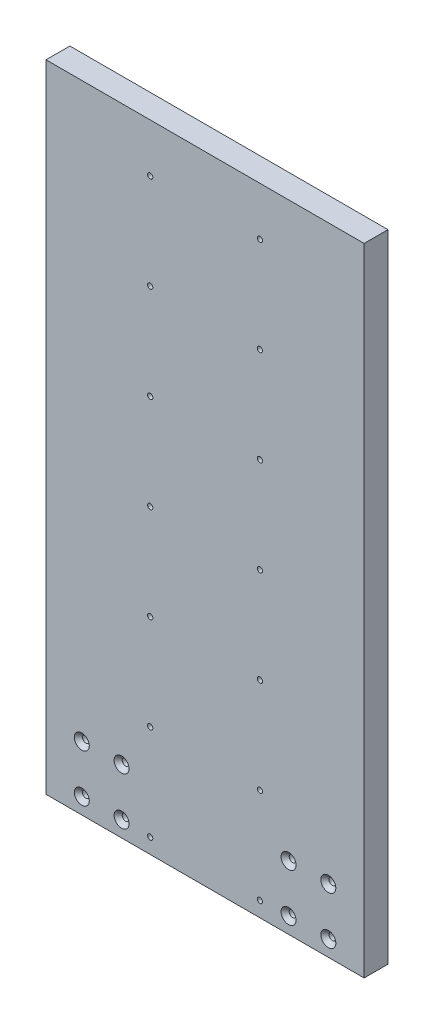
SolidWorks part; units mm, degrees
ref_plane "Front Plane" through (0, 0, 0) normal (0, 0, 1) x (1, 0, 0)
ref_plane "Top Plane" through (0, 0, 0) normal (0, 1, 0) x (1, 0, 0)
ref_plane "Right Plane" through (0, 0, 0) normal (1, 0, 0) x (0, 0, -1)
sketch "Sketch1" plane through (0, 0, 0) normal (0, 0, 1) x (1, 0, 0)
  line L1 (100, 200) -> (-100, 200)
  line L2 (100, 200) -> (100, -200)
  line L3 (100, -200) -> (-100, -200)
  line L4 (-100, 200) -> (-100, -200)
  line L5 (100, 200) -> (-100, -200) construction
  line L6 (100, -200) -> (-100, 200) construction
  point P0 (0, 0)
  dimension "D1" = 200
  dimension "D2" = 400
extrude "Boss-Extrude1" add sketch "Sketch1" along normal blind 15 contours L1 L4 L3 L2
sketch "Sketch3" plane through (0, 0, 15) normal (0, 0, 1) x (1, 0, 0)
  line L0 (-77.5, -190) -> (-77.5, -200)
  line L1 (100, -200) -> (-100, -200) construction
  line L2 (-100, 200) -> (-100, -200) construction
  point P0 (-77.5, -160)
  point P3 (-52.5, -160)
  point P4 (-52.5, -190)
  point P5 (-77.5, -190)
  point P7 (52.5, -160)
  point P8 (77.5, -160)
  point P9 (77.5, -190)
  point P10 (52.5, -190)
  point P22 (0, 0)
  point P23 (-52.5, -70)
  point P24 (52.5, -70)
  point P25 (77.5, -70)
  point P26 (77.5, -40)
  point P27 (52.5, -40)
  point P28 (-77.5, -70)
  point P29 (-52.5, -40)
  point P30 (-77.5, -40)
  dimension "D5" = 10
  dimension "D6" = 22.5
  dimension "D1" = 2
  dimension "D2" = 2
  dimension "D3" = 2
  dimension "D4" = 2
hole_wizard "CSK for M4 Flat Head Machine Screw1" positions "Sketch3" profile "Sketch4" countersink size "M4" standard "ANSI Metric"
sketch "Sketch4" plane through (-77.5, -160, 15) normal (1, 0, 0) x (0, -1, 0)
  line L0 (0, 0) -> (0, 15)
  line L1 (0, 15) -> (2.15, 15)
  line L2 (2.15, 15) -> (2.15, 2.55)
  line L3 (2.15, 2.55) -> (4.7, 0)
  line L5 (4.7, 0) -> (0, 0)
  line L6 (-2.15, 2.55) -> (-4.7, 0) construction
  line L11 (0, -6.35) -> (0, 107.95) construction
  dimension "Thru Hole Dia." = 4.3
  dimension "Thru Hole Depth" = 15
  dimension "Near C'Sink Dia." = 9.4
  dimension "Near C'Sink Angle" = 90
sketch "Sketch5" plane through (0, 0, 15) normal (0, 0, 1) x (1, 0, 0)
  line L0 (100, -200) -> (-100, -200) construction
  circle A0 centre (52.5, -190) radius 2.15 construction
  circle A1 centre (-52.5, -190) radius 4.7 construction
  point P0 (-34.5, -190.5)
  point P1 (34.5, -190.5)
  point P8 (-34.5, -130.5)
  point P10 (34.5, -130.5)
  point P11 (-34.5, -70.5)
  point P12 (34.5, -70.5)
  point P13 (-34.5, -10.5)
  point P14 (34.5, -10.5)
  point P15 (-34.5, 49.5)
  point P16 (34.5, 49.5)
  point P17 (-34.5, 109.5)
  point P18 (34.5, 109.5)
  point P19 (-34.5, 169.5)
  point P20 (34.5, 169.5)
  dimension "D1" = 9.5
  dimension "D2" = 9.5
  dimension "D3" = 18
  dimension "D4" = 18
  dimension "D5" = 7
hole_wizard "M4x0.7 Tapped Hole1" positions "Sketch5" profile "Sketch6" tap size "M4x0.7" standard "ANSI Metric" end condition through all
sketch "Sketch6" plane through (-34.5, -190.5, 15) normal (1, 0, 0) x (0, -1, 0)
  line L0 (0, 0) -> (0, 15)
  line L1 (0, 15) -> (1.65, 15)
  line L2 (1.65, 15) -> (1.65, 0)
  line L5 (1.65, 0) -> (0, 0)
  line L11 (0, -6.35) -> (0, 107.95) construction
  dimension "Thru Tap Drill Dia." = 3.3
  dimension "Thru Tap Drill Depth" = 15
cosmetic thread "Hole Thread1" parameters "D2"=4
cosmetic thread "Hole Thread2" parameters "D2"=4
cosmetic thread "Hole Thread3" parameters "D2"=4
cosmetic thread "Hole Thread4" parameters "D2"=4
cosmetic thread "Hole Thread5" parameters "D2"=4
cosmetic thread "Hole Thread6" parameters "D2"=4
cosmetic thread "Hole Thread7" parameters "D2"=4
cosmetic thread "Hole Thread8" parameters "D2"=4
cosmetic thread "Hole Thread9" parameters "D2"=4
cosmetic thread "Hole Thread10" parameters "D2"=4
cosmetic thread "Hole Thread11" parameters "D2"=4
cosmetic thread "Hole Thread12" parameters "D2"=4
cosmetic thread "Hole Thread13" parameters "D2"=4
cosmetic thread "Hole Thread14" parameters "D2"=4
